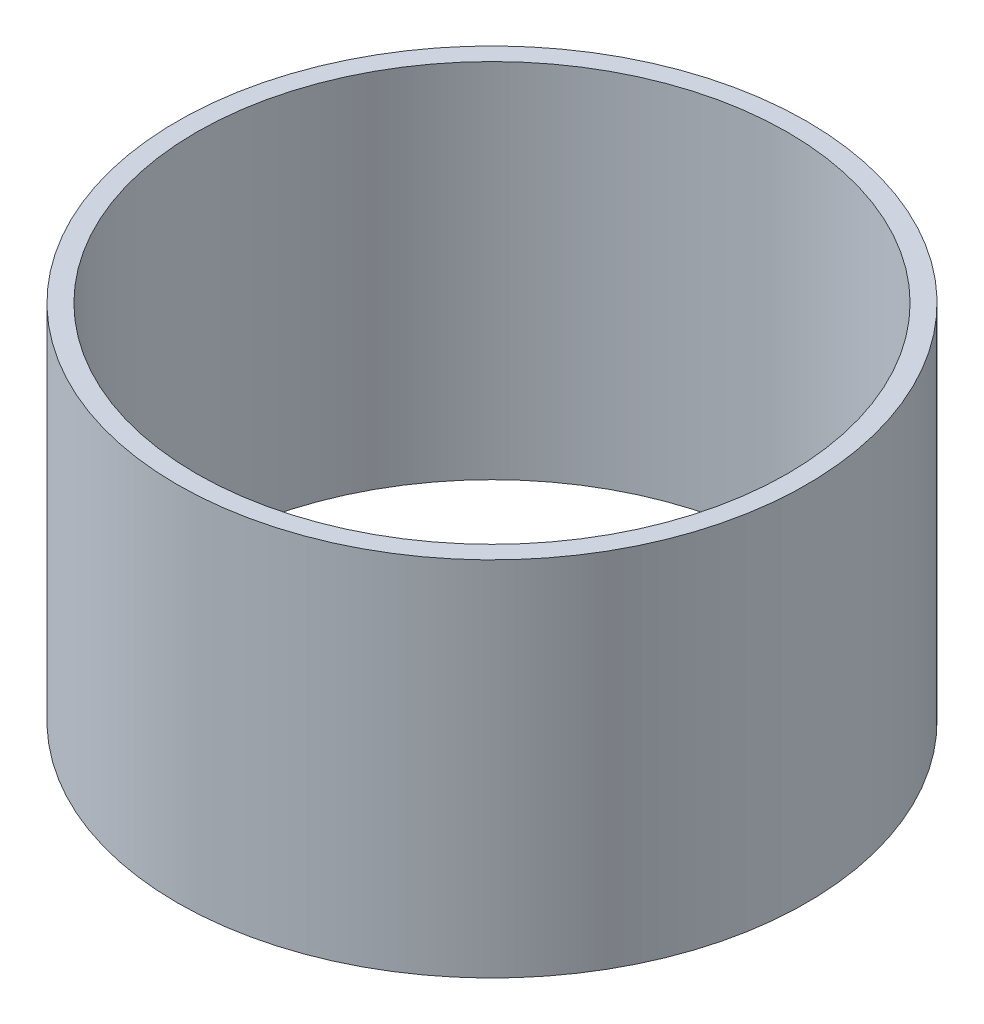
SolidWorks part; units mm, degrees
ref_plane "Front" through (0, 0, 0) normal (0, 0, 1) x (1, 0, 0)
ref_plane "Top" through (0, 0, 0) normal (0, 1, 0) x (1, 0, 0)
ref_plane "Right" through (0, 0, 0) normal (1, 0, 0) x (0, 0, -1)
sketch "Sketch1" plane through (0, 0, 0) normal (0, 1, 0) x (1, 0, 0)
  circle A0 centre (0, 0) radius 10.3688
  circle A1 centre (0, 0) radius 11.0375
  dimension "D1" = 22.075
  dimension "D2" = 20.7375
extrude "Boss-Extrude1" add sketch "Sketch1" along normal blind 12.7
